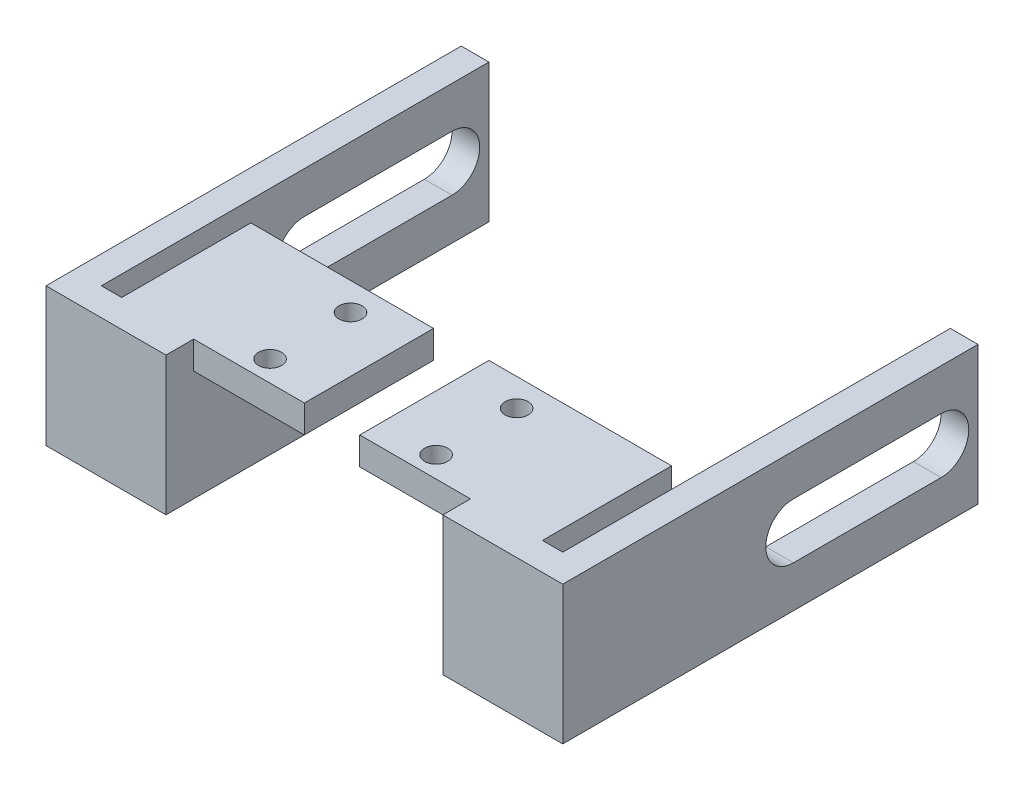
SolidWorks part; units mm, degrees
ref_plane "Front Plane" through (0, 0, 0) normal (0, 0, 1) x (1, 0, 0)
ref_plane "Top Plane" through (0, 0, 0) normal (0, 1, 0) x (1, 0, 0)
ref_plane "Right Plane" through (0, 0, 0) normal (1, 0, 0) x (0, 0, -1)
sketch "Sketch1" plane through (0, 0, 0) normal (1, 0, 0) x (0, 0, -1)
  line L0 (41, 7.5) -> (25, 7.5) construction
  line L1 (0, 0) -> (45, 0)
  line L2 (0, 0) -> (0, 15)
  line L3 (0, 15) -> (45, 15)
  line L4 (45, 0) -> (45, 15)
  line L5 (0, 0) -> (45, 15) construction
  line L6 (0, 15) -> (45, 0) construction
  line L7 (41, 4.5) -> (25, 4.5)
  line L8 (41, 10.5) -> (25, 10.5)
  circle A0 centre (41, 7.5) radius 3.8605 construction
  arc A1 (41, 4.5) -> (41, 10.5) centre (41, 7.5) ccw
  arc A2 (25, 10.5) -> (25, 4.5) centre (25, 7.5) ccw
  point P4 (22.5, 7.5)
  point P8 (33, 7.5)
  dimension "D3" = 7.7209
  dimension "D4" = 4
  dimension "D5" = 3
  dimension "D1" = 45
  dimension "D2" = 15
  dimension "D6" = 16
extrude "mounts_to_cnc" add sketch "Sketch1" along normal blind 3
sketch "Sketch2" plane through (0, 0, 0) normal (0, 1, 0) x (1, 0, 0)
  line L1 (0, 0) -> (-10, 0)
  line L2 (0, 0) -> (0, 17)
  line L3 (0, 17) -> (-10, 17)
  line L4 (-10, 0) -> (-10, 17)
  line L5 (0, 0) -> (-10, 17) construction
  line L6 (0, 17) -> (-10, 0) construction
  point P4 (-5, 8.5)
  dimension "D1" = 10
  dimension "D2" = 17
extrude "wrap_around" add sketch "Sketch2" along normal up to surface (15 mm away) up to face at (1.5, 15, -22.5)
sketch "Sketch4" plane through (0, 15, 0) normal (0, 1, 0) x (1, 0, 0)
  line L0 (3, 45) -> (0, 45) construction
  line L1 (0, 45) -> (-2.2, 45)
  line L2 (0, 45) -> (0, 3)
  line L3 (0, 3) -> (-2.2, 3)
  line L4 (-2.2, 45) -> (-2.2, 3)
  line L5 (0, 45) -> (-2.2, 3) construction
  line L6 (0, 3) -> (-2.2, 45) construction
  line L7 (3, 0) -> (-10, 0) construction
  point P4 (-1.1, 24)
  point P7 (0, 0)
  point P8 (0, 0)
  dimension "D1" = 2.2
  dimension "D2" = 3
extrude "space_for_steel" cut sketch "Sketch4" against normal up to next
sketch "Sketch5" plane through (-10, 0, 0) normal (-1, 0, 0) x (0, 0, 1)
  line L0 (-3, 0) -> (-3, 15) construction
  line L1 (-17, 15) -> (-3, 15)
  line L2 (-17, 15) -> (-17, 12)
  line L3 (-17, 12) -> (-3, 12)
  line L4 (-3, 15) -> (-3, 12)
  line L5 (-17, 15) -> (-3, 12) construction
  line L6 (-17, 12) -> (-3, 15) construction
  point P4 (-10, 13.5)
  dimension "D1" = 3
  dimension "D2" = 0
extrude "level_switch_platform" add sketch "Sketch5" along normal blind 12
sketch "Sketch7" plane through (0, 15, 0) normal (0, 1, 0) x (1, 0, 0)
  line L0 (-22, 17) -> (-2.2, 17) construction
  line L1 (-22, 3) -> (-10, 3) construction
  line L3 (-22, 3) -> (-22, 17) construction
  circle A0 centre (-16, 14) radius 1.25
  circle A1 centre (-16, 5.28) radius 1.25
  point P4 (0, 0)
  dimension "D1" = 8.72
  dimension "D2" = 3
  dimension "D3" = 2.5
  dimension "D5" = 2.28
  dimension "D4" = 6
  dimension "D6" = 6
extrude "switch_mount_holes" cut sketch "Sketch7" against normal up to next
ref_plane "Plane7" through (-25, 0, 0) normal (-1, 0, 0) x (0, 0, 1)
mirror "chiarity_copy" about plane through (-25, 0, 0) normal (-1, 0, 0) of bodies 106
